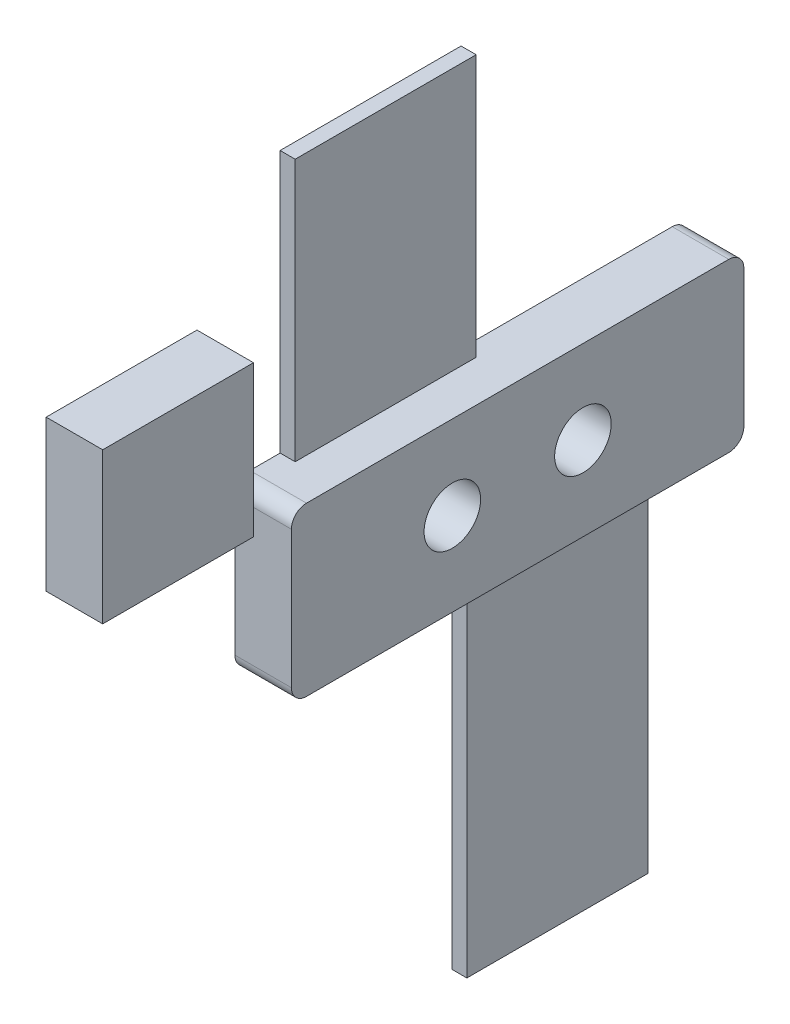
SolidWorks part; units mm, degrees
material "6061-T6 (SS)"
ref_plane "Front Plane" through (0, 0, 0) normal (0, 0, 1) x (1, 0, 0)
ref_plane "Top Plane" through (0, 0, 0) normal (0, 1, 0) x (1, 0, 0)
ref_plane "Right Plane" through (0, 0, 0) normal (1, 0, 0) x (0, 0, -1)
sketch "Sketch1" plane through (0, 0, 0) normal (1, 0, 0) x (0, 0, -1)
  line L1 (-19.05, -7.0485) -> (19.05, -7.0485)
  line L2 (-19.05, -7.0485) -> (-19.05, 7.0485)
  line L3 (-19.05, 7.0485) -> (19.05, 7.0485)
  line L4 (19.05, -7.0485) -> (19.05, 7.0485)
  line L5 (-19.05, -7.0485) -> (19.05, 7.0485) construction
  line L6 (-19.05, 7.0485) -> (19.05, -7.0485) construction
  point P4 (0, 0)
  dimension "D1" = 14.097
  dimension "D2" = 38.1
extrude "Boss-Extrude1" add sketch "Sketch1" along normal blind 4.7625
fillet "Fillet1" radius 1.27 4 edges at (2.3813, 7.0485, 19.05) (2.3813, 7.0485, -19.05) (2.3813, -7.0485, -19.05) (2.3813, -7.0485, 19.05)
sketch "Sketch2" plane through (4.7625, 0, 0) normal (1, 0, 0) x (0, 0, -1)
  line L0 (-19.05, 0) -> (-5.4991, 0) construction
  line L3 (-19.05, 5.7785) -> (-19.05, -5.7785) construction
  line L4 (-5.4991, 0) -> (5.4991, 0) construction
  line L5 (5.4991, 0) -> (19.05, 0) construction
  line L6 (19.05, -5.7785) -> (19.05, 5.7785) construction
  circle A0 centre (-5.4991, 0) radius 2.3813
  circle A1 centre (5.4991, 0) radius 2.3813
  dimension "D1" = 4.7625
  dimension "D2" = 10.9982
extrude "Cut-Extrude1" cut sketch "Sketch2" against normal up to surface (4.7625 mm away) up to face at (0, 0, 0)
sketch "Sketch3" plane through (0, 0, 0) normal (-1, 0, 0) x (0, 0, 1)
  line L1 (34.9411, 19.5204) -> (22.2411, 19.5204)
  line L2 (34.9411, 19.5204) -> (34.9411, 6.8204)
  line L3 (34.9411, 6.8204) -> (22.2411, 6.8204)
  line L4 (22.2411, 19.5204) -> (22.2411, 6.8204)
  dimension "D1" = 12.7
extrude "Boss-Extrude2" add sketch "Sketch3" against normal up to surface (4.7625 mm away) separate body up to face at (4.7625, 0, 3.1179)
sketch "Sketch4" plane through (0, 0, 0) normal (-1, 0, 0) x (0, 0, 1)
  line L0 (15.24, 7.0485) -> (0, 7.0485)
  line L1 (15.24, 7.0485) -> (15.24, 29.1156)
  line L2 (0, 7.0485) -> (0, 29.1156)
  line L3 (15.24, 29.1156) -> (0, 29.1156)
  line L4 (-17.78, 7.0485) -> (17.78, 7.0485) construction
  line L5 (0.7833, -7.0485) -> (-14.4567, -7.0485)
  line L6 (0.7833, -7.0485) -> (0.7833, -37.8281)
  line L7 (-14.4567, -7.0485) -> (-14.4567, -37.8281)
  line L8 (0.7833, -37.8281) -> (-14.4567, -37.8281)
  line L9 (17.78, -7.0485) -> (-17.78, -7.0485) construction
  dimension "D1" = 15.24
extrude "Boss-Extrude3" add sketch "Sketch4" against normal blind 1.27
sketch "Sketch5" [suppressed] plane through (4.7625, 0, 0) normal (1, 0, 0) x (0, 0, -1)
  line L0 (-17.78, 7.0485) -> (17.78, 7.0485)
  line L1 (19.05, 5.7785) -> (19.05, -5.7785)
  line L2 (17.78, -7.0485) -> (-17.78, -7.0485)
  line L3 (-19.05, -5.7785) -> (-19.05, 5.7785)
  arc A0 (17.78, 7.0485) -> (19.05, 5.7785) centre (17.78, 5.7785) cw
  arc A1 (19.05, 5.7785) -> (17.78, 7.0485) centre (17.78, 5.7785) ccw construction
  arc A2 (19.05, -5.7785) -> (17.78, -7.0485) centre (17.78, -5.7785) cw
  arc A3 (-17.78, -7.0485) -> (-19.05, -5.7785) centre (-17.78, -5.7785) cw
  arc A4 (-19.05, 5.7785) -> (-17.78, 7.0485) centre (-17.78, 5.7785) cw
extrude "Cut-Extrude2" [suppressed] cut sketch "Sketch5" against normal blind 3.175
